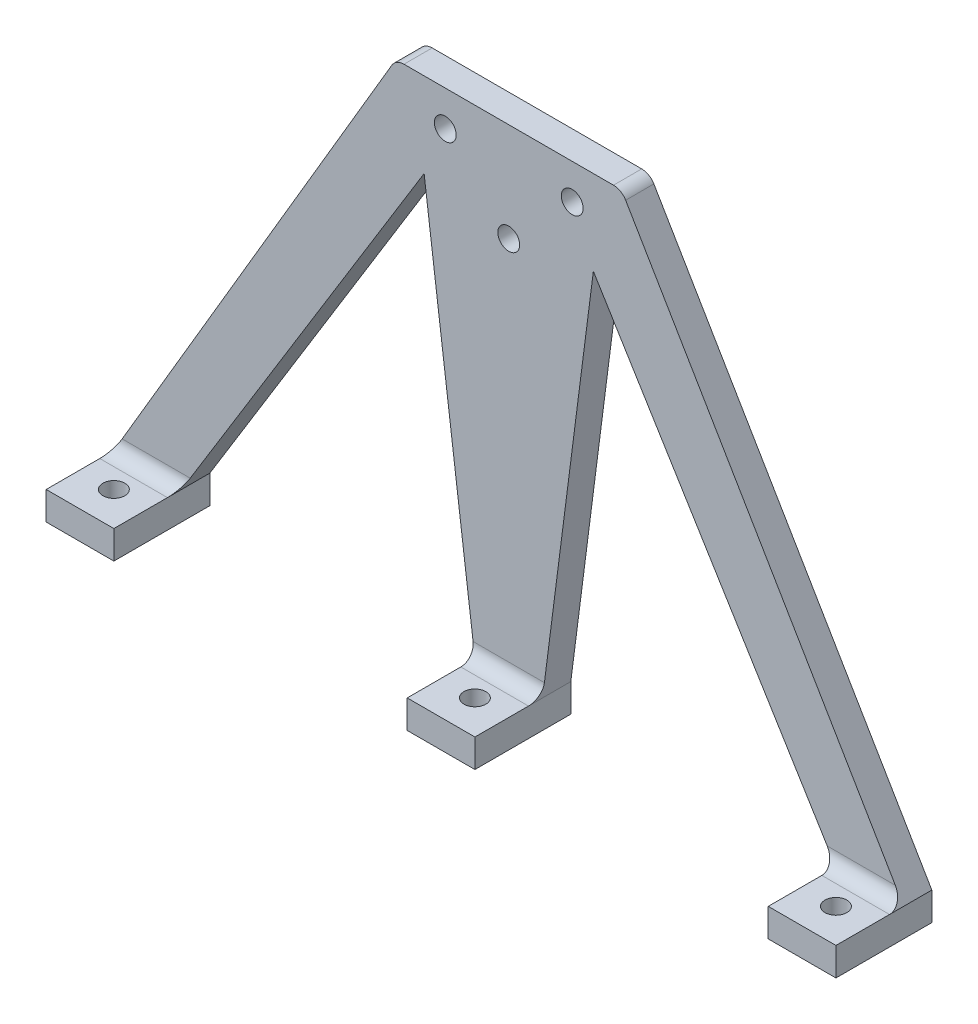
SolidWorks part; units mm, degrees
ref_plane "Front Plane" through (0, 0, 0) normal (0, 0, 1) x (1, 0, 0)
ref_plane "Top Plane" through (0, 0, 0) normal (0, 1, 0) x (1, 0, 0)
ref_plane "Right Plane" through (0, 0, 0) normal (1, 0, 0) x (0, 0, -1)
sketch "Sketch1" plane through (0, 0, 0) normal (0, 0, 1) x (1, 0, 0)
  line L1 (0, 0) -> (112, 0)
  line L2 (0, 0) -> (0, -72)
  line L3 (0, -72) -> (112, -72)
  line L4 (112, 0) -> (112, -72)
  dimension "D1" = 112
  dimension "D2" = 72
extrude "Boss-Extrude1" add sketch "Sketch1" along normal blind 4
sketch "Sketch2" plane through (0, 0, 4) normal (0, 0, 1) x (1, 0, 0)
  line L0 (0, -72) -> (112, -72) construction
  line L1 (0, -72) -> (9.6, -72)
  line L2 (0, -72) -> (0, -68)
  line L3 (0, -68) -> (9.6, -68)
  line L4 (9.6, -72) -> (9.6, -68)
  line L6 (102.4, -72) -> (112, -72)
  line L7 (102.4, -72) -> (102.4, -68)
  line L8 (102.4, -68) -> (112, -68)
  line L9 (112, -72) -> (112, -68)
  line L10 (51.2, -72) -> (60.8, -72)
  line L11 (51.2, -72) -> (51.2, -68)
  line L12 (51.2, -68) -> (60.8, -68)
  line L13 (60.8, -72) -> (60.8, -68)
  dimension "D4" = 9.6
  dimension "D1" = 9.6
  dimension "D5" = 9.6
  dimension "D6" = 51.2
  dimension "D7" = 4
  dimension "D8" = 4
  dimension "D9" = 4
  dimension "D2" = 102.4
extrude "Boss-Extrude2" add sketch "Sketch2" along normal blind 9.6
sketch "Sketch3" plane through (0, -68, 0) normal (0, 1, 0) x (1, 0, 0)
  line L0 (9.6, -13.6) -> (0, -13.6) construction
  line L1 (60.8, -13.6) -> (51.2, -13.6) construction
  line L2 (112, -13.6) -> (102.4, -13.6) construction
  line L3 (0, -13.6) -> (0, -4) construction
  line L4 (51.2, -13.6) -> (51.2, -4) construction
  line L5 (102.4, -13.6) -> (102.4, -4) construction
  circle A0 centre (4.8, -8.8) radius 1.55
  circle A1 centre (56, -8.8) radius 1.55
  circle A2 centre (107.2, -8.8) radius 1.55
  dimension "D1" = 3.1
  dimension "D2" = 3.1
  dimension "D3" = 3.1
  dimension "D4" = 4.8
  dimension "D5" = 4.8
  dimension "D6" = 4.8
  dimension "D7" = 4.8
  dimension "D8" = 4.8
  dimension "D9" = 4.8
extrude "Cut-Extrude1" cut sketch "Sketch3" against normal blind 9.6
sketch "Sketch4" plane through (0, 0, 4) normal (0, 0, 1) x (1, 0, 0)
  line L0 (112, 0) -> (0, 0) construction
  circle A0 centre (47, -5) radius 1.55
  circle A1 centre (65, -5) radius 1.55
  circle A2 centre (56, -14) radius 1.55
  point P8 (56, 0)
  dimension "D6" = 3.1
  dimension "D7" = 3.1
  dimension "D8" = 3.1
  dimension "D1" = 18
  dimension "D2" = 9
  dimension "D3" = 9
  dimension "D4" = 5
  dimension "D5" = 5
extrude "Cut-Extrude2" cut sketch "Sketch4" against normal blind 9.6
sketch "Sketch5" plane through (0, 0, 4) normal (0, 0, 1) x (1, 0, 0)
  line L0 (0, -68) -> (0, 0)
  line L1 (0, 0) -> (40, 0)
  line L2 (112, 0) -> (0, 0) construction
  line L3 (40, 0) -> (0, -68)
  line L4 (72, 0) -> (112, -68)
  line L5 (56, 0) -> (56, -7.382) construction
  line L8 (112, 0) -> (72, 0)
  line L9 (112, -68) -> (112, 0)
  dimension "D1" = 40
extrude "Cut-Extrude4" cut sketch "Sketch5" against normal blind 9.6
sketch "Sketch6" plane through (0, 0, 4) normal (0, 0, 1) x (1, 0, 0)
  line L0 (9.6, -68) -> (44, -12)
  line L1 (44, -12) -> (51.2, -68)
  line L2 (51.2, -68) -> (51.2, -72)
  line L3 (51.2, -72) -> (9.6, -72)
  line L4 (9.6, -72) -> (9.6, -68)
  line L5 (56, 0) -> (56, -8.7021) construction
  line L6 (72, 0) -> (40, 0) construction
  line L7 (102.4, -72) -> (102.4, -68)
  line L8 (60.8, -68) -> (60.8, -72)
  line L9 (60.8, -72) -> (102.4, -72)
  line L10 (68, -12) -> (60.8, -68)
  line L11 (102.4, -68) -> (68, -12)
  dimension "D1" = 12
  dimension "D2" = 12
extrude "Cut-Extrude5" cut sketch "Sketch6" against normal blind 9.6
fillet "Fillet1" radius 2 3 edges at (107.2, -68, 4) (56, -68, 4) (4.8, -68, 4)
fillet "Fillet2" radius 2 2 edges at (72, 0, 2) (40, 0, 2)
equation "\"D1@Sketch1\"=102.4+9.6"
equation "\"D2@Sketch1\"=0.8*90"
equation "\"D6@Sketch2\"=102.4/2"
equation "\"D2@Sketch3\"=\"D1@Sketch3\""
equation "\"D3@Sketch3\"=\"D1@Sketch3\""
equation "\"D5@Sketch3\"=\"D4@Sketch3\""
equation "\"D6@Sketch3\"=\"D4@Sketch3\""
equation "\"D5@Sketch2\"=\"D4@Sketch2\""
equation "\"D1@Sketch2\"=\"D4@Sketch2\""
equation "\"D7@Sketch3\"=4.8"
equation "\"D8@Sketch3\"=\"D4@Sketch3\""
equation "\"D9@Sketch3\"=\"D4@Sketch3\""
equation "\"D5@Sketch4\"=\"D4@Sketch4\""
